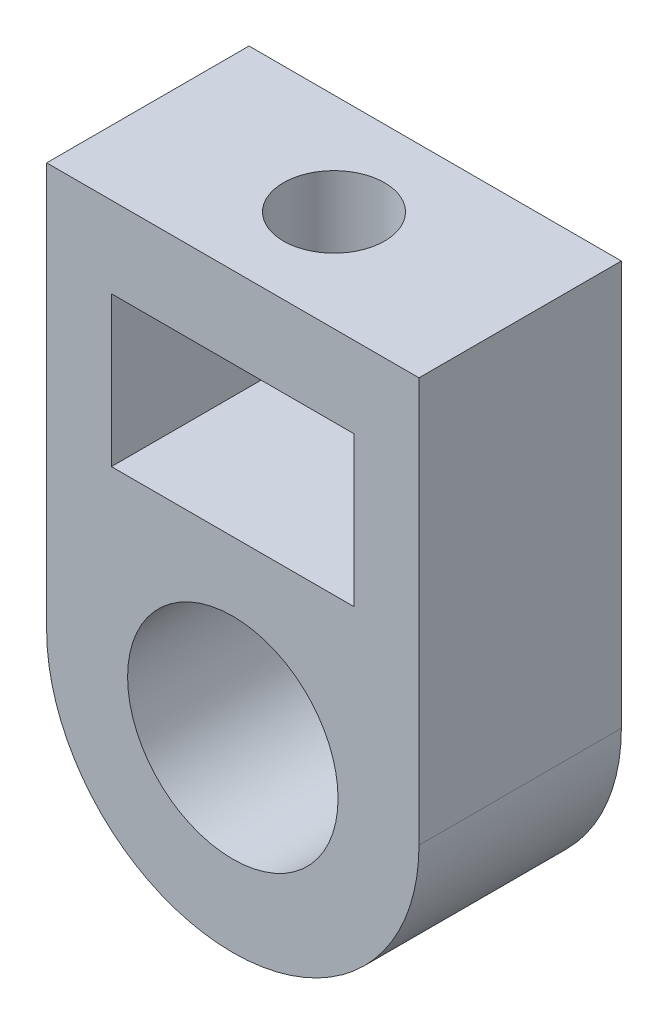
SolidWorks part; units mm, degrees
material "ABS"
ref_plane "Front Plane" through (0, 0, 0) normal (0, 0, 1) x (1, 0, 0)
ref_plane "Top Plane" through (0, 0, 0) normal (0, 1, 0) x (1, 0, 0)
ref_plane "Right Plane" through (0, 0, 0) normal (1, 0, 0) x (0, 0, -1)
sketch "Sketch1" plane through (0, 0, 0) normal (0, 0, 1) x (1, 0, 0)
  line L0 (-4.6, 0) -> (-4.6, 10)
  line L1 (-4.6, 10) -> (4.6, 10)
  line L2 (4.6, 10) -> (4.6, 0)
  circle A0 centre (0, 0) radius 2.6
  arc A1 (-4.6, 0) -> (4.6, 0) centre (0, 0) ccw
  dimension "D1" = 5.2
  dimension "D2" = 2
  dimension "D3" = 10
extrude "Boss-Extrude1" add sketch "Sketch1" along normal blind 5 contours L0 A1 L2 L1 A0
sketch "Sketch2" plane through (0, 10, 0) normal (0, 1, 0) x (1, 0, 0)
  line L0 (-4.6, -5) -> (-4.6, 0) construction
  line L1 (-4.6, -5) -> (4.6, -5) construction
  circle A0 centre (0, -2.5) radius 1.25
  point P4 (-4.6, -2.5)
  point P5 (0, 0)
  point P8 (0, -5)
  dimension "D1" = 2.5
extrude "Cut-Extrude1" cut sketch "Sketch2" against normal blind 2
sketch "Sketch3" plane through (0, 0, 5) normal (0, 0, 1) x (1, 0, 0)
  line L0 (-4.6, 10) -> (4.6, 10) construction
  line L1 (-3, 8) -> (3, 8)
  line L2 (-3, 8) -> (-3, 4.3)
  line L3 (-3, 4.3) -> (3, 4.3)
  line L4 (3, 8) -> (3, 4.3)
  line L5 (-3, 8) -> (3, 4.3) construction
  line L6 (-3, 4.3) -> (3, 8) construction
  point P0 (0, 6.15)
  point P7 (0, 10)
  point P8 (0, 8)
  dimension "D1" = 3.7
  dimension "D2" = 6
  dimension "D3" = 2
extrude "Cut-Extrude2" cut sketch "Sketch3" against normal up to surface (5 mm away) up to face at (2.6, 0, 0)
